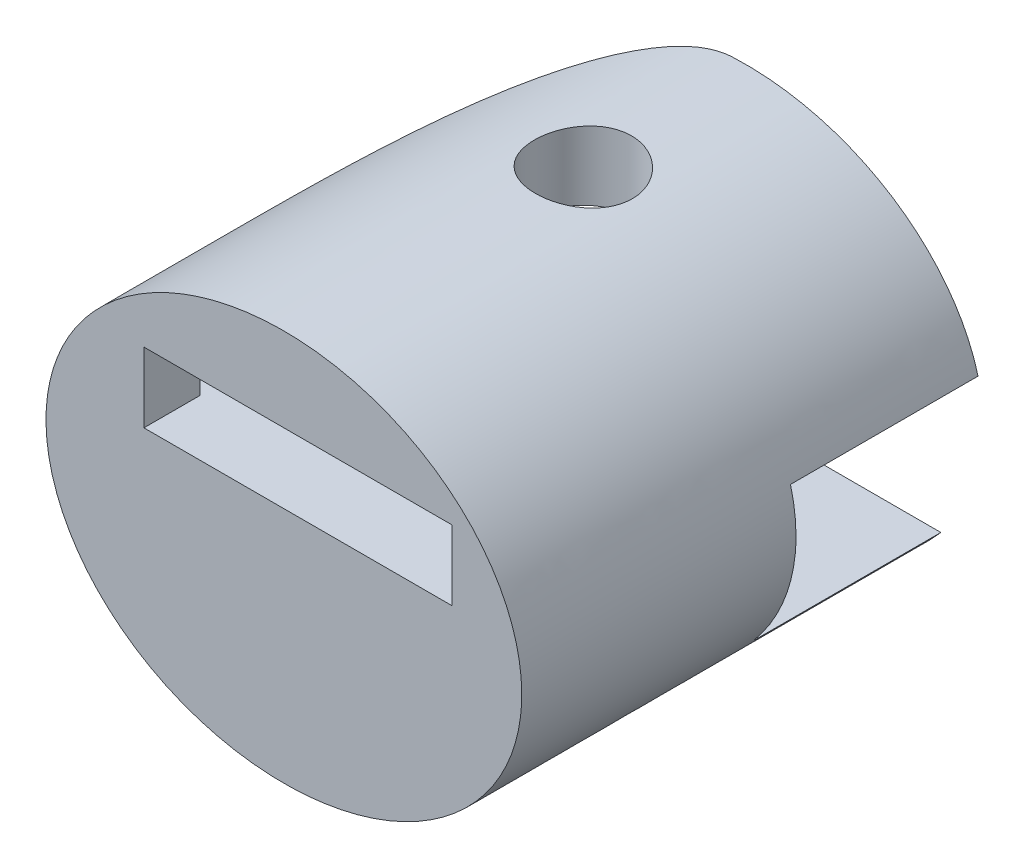
SolidWorks part; units mm, degrees
ref_plane "Front Plane" through (0, 0, 0) normal (0, 0, 1) x (1, 0, 0)
ref_plane "Top Plane" through (0, 0, 0) normal (0, 1, 0) x (1, 0, 0)
ref_plane "Right Plane" through (0, 0, 0) normal (1, 0, 0) x (0, 0, -1)
sketch "Sketch1" plane through (0, 0, 0) normal (0, 0, 1) x (1, 0, 0)
  ellipse E0 centre (0, 0) end of major axis (8.5, 0) minor radius 7
  dimension "D1" = 14
  dimension "D2" = 17
extrude "Boss-Extrude1" add sketch "Sketch1" along normal blind 4
sketch "Sketch5" plane through (0, 0, 0) normal (0, 0, -1) x (-1, 0, 0)
  ellipse E0 centre (0, 0) end of major axis (-8.5, 0) minor radius 7
  ellipse E1 centre (0, 0) end of major axis (-8.5, 0) minor radius 7 construction
extrude "Boss-Extrude2" add sketch "Sketch5" along normal blind 12.5
ref_plane "Plane1" through (0, 10, 0) normal (0, 1, 0) x (1, 0, 0)
sketch "Sketch6" plane through (0, 10, 0) normal (0, 1, 0) x (1, 0, 0)
  line L0 (-8.5, 12.5) -> (-8.5, -4) construction
  line L1 (-8.5, -4) -> (8.5, -4) construction
  line L4 (-8.5, 12.5) -> (-8.5, 0)
  line L5 (8.5, 12.5) -> (-8.5, 12.5) construction
  line L6 (-8.5, 0) -> (-6.5, 0)
  line L9 (-8.5, 12.5) -> (-0.5, 12.5)
  circle A0 centre (0.2, 6.5) radius 1.75
  spline S0 degree 3 poles (-6.5, 0) (-6.5, 5.077) (-3.8539, 12.5) (-0.5, 12.5) knots 0 0 0 0 1 1 1 1
  dimension "D4" = 8
  dimension "D1" = 3.5
  dimension "D2" = 8.7
  dimension "D3" = 10.5
  dimension "D5" = 2
  dimension "D6" = 4
extrude "Cut-Extrude1" cut sketch "Sketch6" against normal blind 20
ref_plane "Plane2" through (0, 0, -12.5) normal (0, 0, 1) x (1, 0, 0)
sketch "Sketch8" plane through (0, 0, -12.5) normal (0, 0, 1) x (1, 0, 0)
  line L0 (0, 7) -> (8.5, 7) construction
  line L1 (8.5, 7) -> (8.5, -7) construction
  line L2 (8.5, -7) -> (-8.5, -7) construction
  line L3 (-8.5, -7) -> (-8.5, 7) construction
  line L4 (-8.5, 7) -> (0, 7) construction
  line L5 (-8.5, 1.5) -> (8.5, 1.5)
  line L6 (-8.5, -4) -> (8.5, -4)
  line L7 (-3.3827, 1.5) -> (-3.3827, -7) construction
  line L8 (-5.9738, -4) -> (-5.9738, -7) construction
  line L9 (-8.5, -4) -> (-8.5, 1.5)
  line L10 (8.5, -4) -> (8.5, 1.5)
  ellipse E0 centre (0, 0) end of major axis (8.5, 0) minor radius 7 construction
  ellipse E1 centre (0, 0) end of major axis (8.5, 0) minor radius 7 construction
  dimension "D1" = 8.5
  dimension "D2" = 3
extrude "Cut-Extrude4" cut sketch "Sketch8" along normal blind 6.7
sketch "Sketch9" plane through (0, 0, 4) normal (0, 0, 1) x (1, 0, 0)
  line L0 (0, 7) -> (8.5, 7) construction
  line L1 (8.5, 7) -> (8.5, -7) construction
  line L2 (8.5, -7) -> (-8.5, -7) construction
  line L3 (-8.5, -7) -> (-8.5, 7) construction
  line L4 (-8.5, 7) -> (0, 7) construction
  line L5 (-5, 4) -> (6, 4)
  line L6 (-5, 1.5) -> (6, 1.5)
  line L7 (-0.8637, 4) -> (-0.8637, 7) construction
  line L8 (0.5, 1.5) -> (0.5, 7) construction
  line L9 (6, 4) -> (8.5, 4) construction
  line L10 (6, 1.5) -> (8.5, 1.5) construction
  line L11 (-5, 4) -> (-5, 1.5)
  line L12 (6, 4) -> (6, 1.5)
  ellipse E0 centre (0, 0) end of major axis (8.5, 0) minor radius 7 construction
  ellipse E1 centre (0, 0) end of major axis (8.5, 0) minor radius 7 construction
  dimension "D1" = 3
  dimension "D2" = 5.5
  dimension "D3" = 2.5
  dimension "D4" = 2.5
  dimension "D5" = 11
  dimension "D6" = 11
extrude "Cut-Extrude5" cut sketch "Sketch9" against normal blind 5.5
ref_plane "Plane3" through (0, -4, 0) normal (0, 1, 0) x (1, 0, 0)
sketch "Sketch10" plane through (0, -4, 0) normal (0, 1, 0) x (1, 0, 0)
  line L0 (6.9755, 5.8) -> (5.7255, 5.8) construction
  line L1 (1.8039, 5.8) -> (6.9755, 5.8) construction
  line L2 (-8.5, 0) -> (3.5, 0)
  line L3 (5.7255, 5.8) -> (3.5, 0)
  line L4 (5.7255, 5.8) -> (-8.5, 5.8)
  line L5 (-8.5, 5.8) -> (-8.5, 0)
  dimension "D1" = 1.25
  dimension "D2" = 12
extrude "Cut-Extrude7" cut sketch "Sketch10" along normal blind 5.5
ref_plane "Plane4" through (0, 1.5, 0) normal (0, -1, 0) x (-1, 0, 0)
sketch "Sketch11" plane through (0, 1.5, 0) normal (0, -1, 0) x (-1, 0, 0)
  line L0 (8.5, -4) -> (8.5, -2) construction
  line L1 (-8.5, -4) -> (8.5, -4) construction
  line L2 (-0.2, 6.5) -> (-0.2, 12.5)
  line L3 (8.5, 1.5) -> (8.5, -2)
  line L4 (-6, -2) -> (-6, 1.5)
  line L5 (-6, -2) -> (8.5, -2)
  line L6 (-0.2, 6.5) -> (-6, 1.5)
  line L8 (-8.9106, 12.5) -> (8.9106, 12.5) construction
  line L9 (-0.2, 12.5) -> (8.5, 12.5)
  line L10 (8.5, 12.5) -> (8.5, 1.5)
  circle A0 centre (-0.2, 6.5) radius 1.75 construction
  circle A1 centre (-0.2, 6.5) radius 1.75 construction
  dimension "D1" = 14.5
  dimension "D2" = 2
extrude "Cut-Extrude8" cut sketch "Sketch11" against normal blind 3
scale "Scale1" bodies to scale 111 scale about centroid uniform scaling yes scale factor 2
